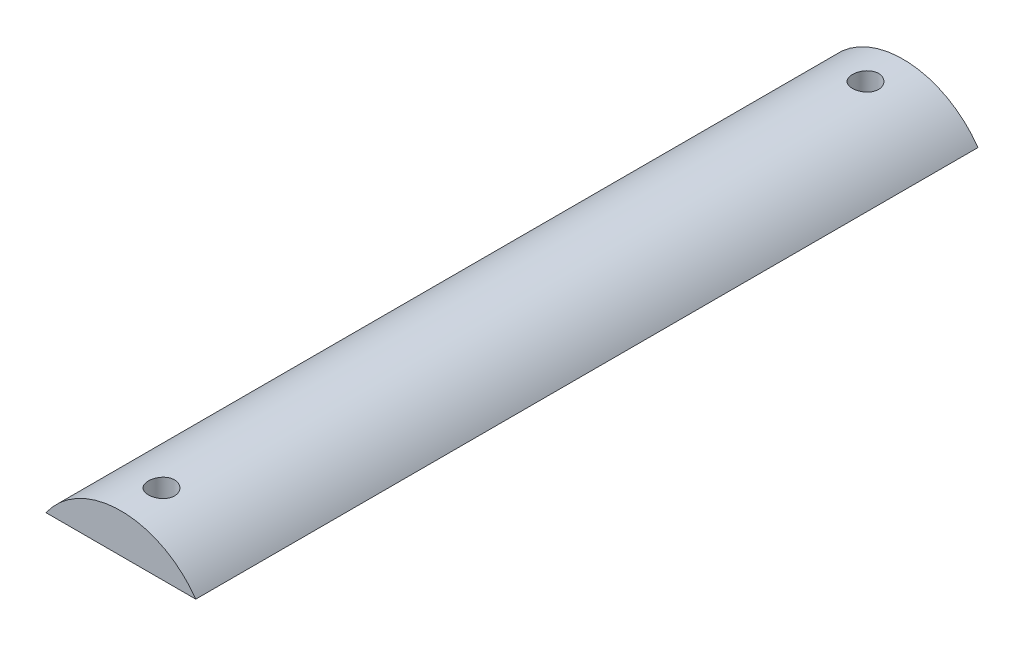
SolidWorks part; units mm, degrees
material "ABS"
ref_plane "Front Plane" through (0, 0, 0) normal (0, 0, 1) x (1, 0, 0)
ref_plane "Top Plane" through (0, 0, 0) normal (0, 1, 0) x (1, 0, 0)
ref_plane "Right Plane" through (0, 0, 0) normal (1, 0, 0) x (0, 0, -1)
sketch "Sketch1" plane through (0, 0, 0) normal (0, 0, 1) x (1, 0, 0)
  line L2 (-5.7446, 4) -> (5.7446, 4)
  line L3 (-5.7446, -4) -> (5.7446, -4)
  circle A0 centre (0, 0) radius 7
extrude "Boss-Extrude1" add sketch "Sketch1" along normal blind 60 contours L2 A0
sketch "Sketch2" plane through (0, 4, 0) normal (0, -1, 0) x (1, 0, 0)
  line L0 (-0.1926, 0) -> (-0.1926, 3) construction
  line L1 (-5.7446, 0) -> (5.7446, 0) construction
  line L2 (-0.1926, 3) -> (-0.1926, 57) construction
  line L3 (-2.502, 57) -> (-1.3473, 55)
  line L4 (-2.502, 3) -> (-1.3473, 1)
  line L5 (-1.3473, 1) -> (0.9621, 1)
  line L6 (0.9621, 1) -> (2.1168, 3)
  line L7 (2.1168, 3) -> (0.9621, 5)
  line L8 (0.9621, 5) -> (-1.3473, 5)
  line L9 (-1.3473, 5) -> (-2.502, 3)
  line L10 (-1.3473, 55) -> (0.9621, 55)
  line L11 (0.9621, 55) -> (2.1168, 57)
  line L12 (2.1168, 57) -> (0.9621, 59)
  line L13 (0.9621, 59) -> (-1.3473, 59)
  line L14 (-1.3473, 59) -> (-2.502, 57)
  circle A0 centre (-0.1926, 3) radius 2 construction
  circle A1 centre (-0.1926, 57) radius 2 construction
  dimension "D1" = 2
extrude "Cut-Extrude1" cut sketch "Sketch2" against normal blind 1 and the other way blind 9
sketch "Sketch3" plane through (0, 5, 0) normal (0, -1, 0) x (1, 0, 0)
  circle A0 centre (0, 2.8888) radius 1
  circle A1 centre (0, 56.8888) radius 1
  dimension "D1" = 2
extrude "Cut-Extrude2" cut sketch "Sketch3" against normal through all and the other way through all
